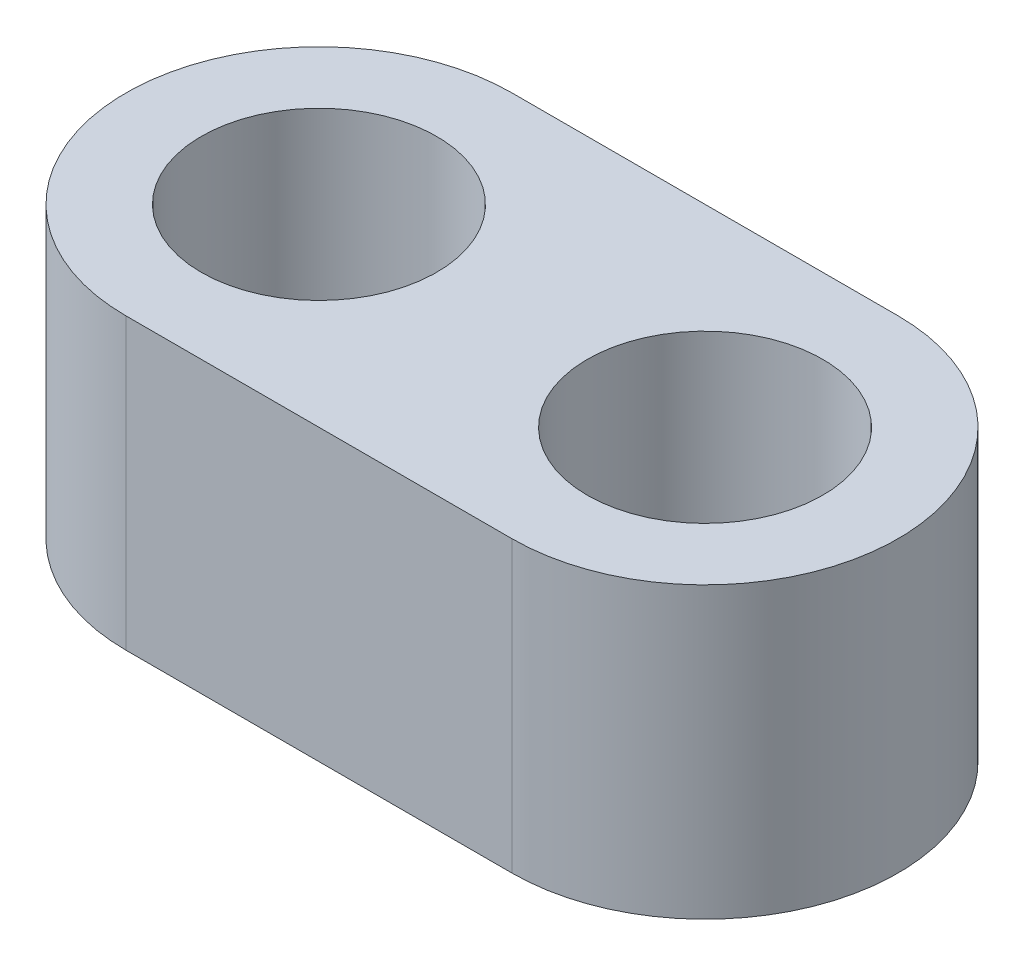
SolidWorks part; units mm, degrees
ref_plane "Front" through (0, 0, 0) normal (0, 0, 1) x (1, 0, 0)
ref_plane "Top" through (0, 0, 0) normal (0, 1, 0) x (1, 0, 0)
ref_plane "Right" through (0, 0, 0) normal (1, 0, 0) x (0, 0, -1)
sketch "Sketch1" plane through (0, 0, 0) normal (0, 1, 0) x (1, 0, 0)
  line L0 (0, 0) -> (20, 0) construction
  line L1 (0, 10) -> (20, 10)
  line L2 (0, -10) -> (20, -10)
  circle A0 centre (0, 0) radius 6.1
  circle A1 centre (20, 0) radius 6.1
  arc A2 (0, 10) -> (0, -10) centre (0, 0) ccw
  arc A3 (20, -10) -> (20, 10) centre (20, 0) ccw
  point P5 (10, 0)
  dimension "D1" = 20
  dimension "D2" = 12.2
  dimension "D3" = 12.2
  dimension "D4" = 20
extrude "Boss-Extrude1" add sketch "Sketch1" along normal blind 15
